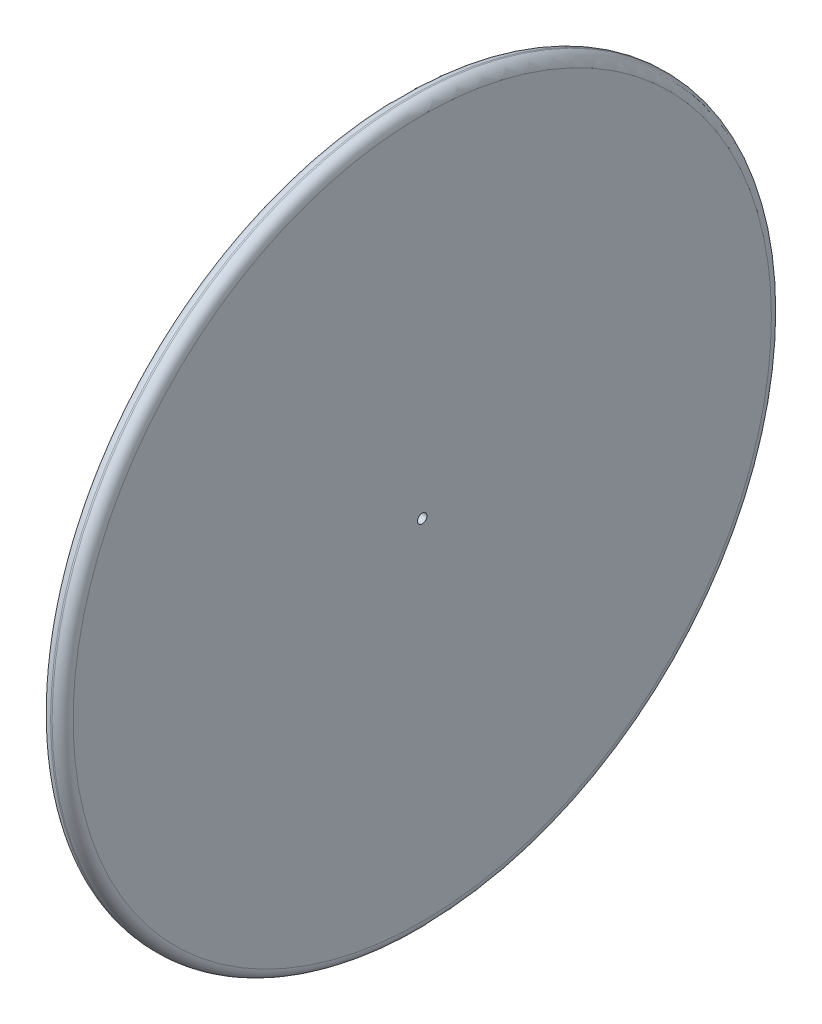
SolidWorks part; units mm, degrees
material "Massless Material"
ref_plane "Front Plane" through (0, 0, 0) normal (0, 0, 1) x (1, 0, 0)
ref_plane "Top Plane" through (0, 0, 0) normal (0, 1, 0) x (1, 0, 0)
ref_plane "Right Plane" through (0, 0, 0) normal (1, 0, 0) x (0, 0, -1)
sketch "Sketch1" plane through (0, 0, 0) normal (1, 0, 0) x (0, 0, -1)
  circle A0 centre (0, 0) radius 3.9878
  circle A1 centre (0, 0) radius 304.8
  dimension "D1" = 7.9756
  dimension "D2" = 609.6
extrude "Boss-Extrude1" add sketch "Sketch1" along normal blind 19.05
fillet "Fillet4" radius 8.89 2 edges at (0, 0, -304.8) (19.05, 0, -304.8)
